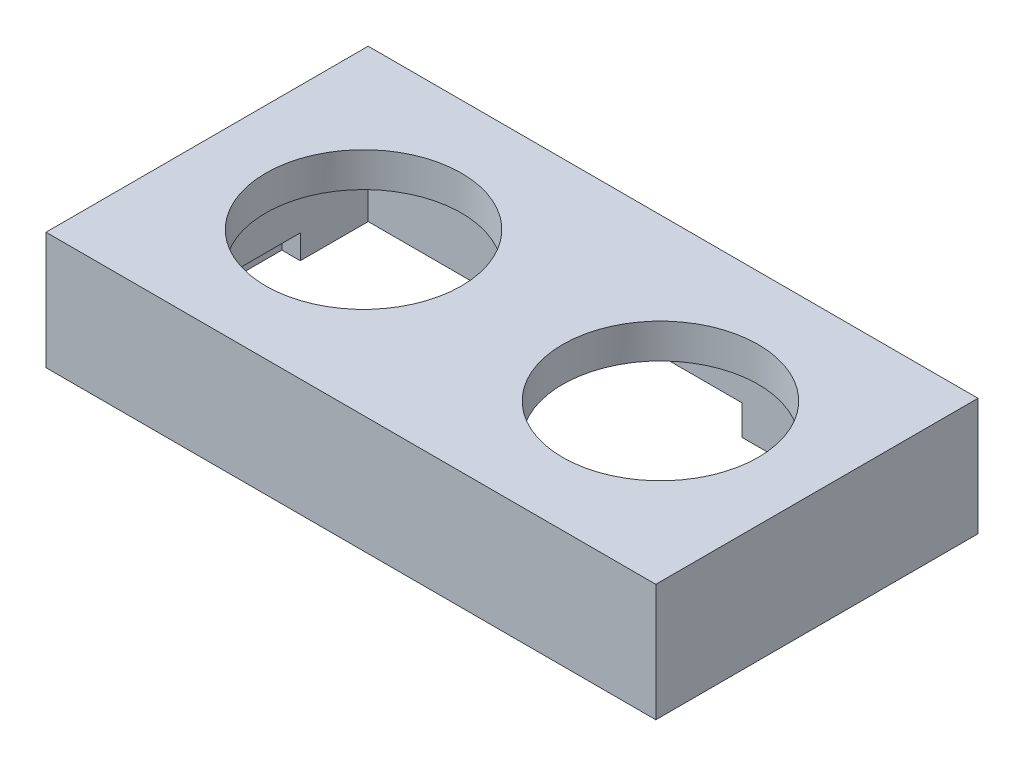
SolidWorks part; units mm, degrees
ref_plane "Front Plane" through (0, 0, 0) normal (0, 0, 1) x (1, 0, 0)
ref_plane "Top Plane" through (0, 0, 0) normal (0, 1, 0) x (1, 0, 0)
ref_plane "Right Plane" through (0, 0, 0) normal (1, 0, 0) x (0, 0, -1)
sketch "Sketch1" plane through (0, 0, 0) normal (0, 0, 1) x (1, 0, 0)
  line L0 (-44.704, 0) -> (44.704, 0) construction
  line L1 (-44.704, -25.8099) -> (44.704, -25.8099)
  line L2 (-44.704, -25.8099) -> (-44.704, 25.8099)
  line L3 (-44.704, 25.8099) -> (44.704, 25.8099)
  line L4 (44.704, -25.8099) -> (44.704, 25.8099)
  line L5 (-44.704, -25.8099) -> (44.704, 25.8099) construction
  line L6 (-44.704, 25.8099) -> (44.704, -25.8099) construction
  line L7 (-44.704, 7.8099) -> (44.704, 7.8099)
  line L8 (0, 0) -> (0, 25.8099) construction
  line L9 (-14.9309, 1.288) -> (-51.3431, 22.3106)
  line L10 (-23.5, 0.6099) -> (23.5, 0.6099)
  line L11 (-23.5, 0.6099) -> (-23.5, 15.0099)
  line L12 (-23.5, 15.0099) -> (23.5, 15.0099)
  line L13 (23.5, 0.6099) -> (23.5, 15.0099)
  line L14 (-23.5, 0.6099) -> (23.5, 15.0099) construction
  line L15 (-23.5, 15.0099) -> (23.5, 0.6099) construction
  line L16 (-23.5, 15.0099) -> (23.5, 15.0099)
  line L17 (-23.5, 15.0099) -> (-23.5, 18.0099)
  line L18 (-23.5, 18.0099) -> (23.5, 18.0099)
  line L19 (23.5, 15.0099) -> (23.5, 18.0099)
  line L20 (-14.9309, 1.288) -> (-8.5809, 12.2866)
  line L21 (-51.3431, 22.3106) -> (-44.9931, 33.3091)
  line L22 (-8.5809, 12.2866) -> (-44.9931, 33.3091)
  line L23 (-14.9309, 1.288) -> (-44.9931, 33.3091) construction
  line L24 (-51.3431, 22.3106) -> (-8.5809, 12.2866) construction
  line L25 (14.9309, 1.288) -> (51.3431, 22.3106)
  line L26 (-26.5, -2.3901) -> (26.5, -2.3901)
  line L27 (-26.5, -2.3901) -> (-26.5, 18.0099)
  line L28 (-26.5, 18.0099) -> (26.5, 18.0099)
  line L29 (26.5, -2.3901) -> (26.5, 18.0099)
  line L30 (-26.5, -2.3901) -> (26.5, 18.0099) construction
  line L31 (-26.5, 18.0099) -> (26.5, -2.3901) construction
  line L32 (8.5809, 12.2866) -> (44.9931, 33.3091)
  circle A0 centre (-44.704, 25.8099) radius 3.175
  circle A1 centre (44.704, 25.8099) radius 3.175
  circle A2 centre (-44.704, 25.8099) radius 6.35
  circle A3 centre (44.704, 25.8099) radius 6.35
  point P0 (0, 0)
  point P16 (0, 7.8099)
  point P24 (-29.962, 17.2986)
  point P25 (0, 7.8099)
  dimension "D3" = 6.35
  dimension "D4" = 6.35
  dimension "D5" = 12.7
  dimension "D6" = 12.7
  dimension "D1" = 89.408
  dimension "D2" = 30
  dimension "D7" = 18
  dimension "D8" = 47
  dimension "D9" = 7.2
  dimension "D10" = 3
  dimension "D11" = 30
  dimension "D12" = 12.7
  dimension "D13" = 53
sketch "Sketch2" plane through (0, 0, 0) normal (0, 0, 1) x (1, 0, 0)
  line L0 (-44.704, 7.8099) -> (44.704, 7.8099) construction
  line L1 (14.9309, 1.288) -> (51.3431, 22.3106) construction
  line L2 (-23.5, 15.0099) -> (23.5, 15.0099) construction
  line L3 (23.5, 0.6099) -> (23.5, 15.0099) construction
  line L5 (23.5, 7.8099) -> (26.5, 7.8099)
  line L6 (-23.5, 7.8099) -> (23.5, 7.8099)
  line L12 (-51.3431, 22.3106) -> (-14.9309, 1.288)
  line L13 (-44.9931, 33.3091) -> (-51.3431, 22.3106)
  line L14 (-8.5809, 12.2866) -> (-44.9931, 33.3091)
  line L15 (-14.9309, 1.288) -> (-8.5809, 12.2866)
  line L16 (-51.3431, 22.3106) -> (-26.5, 7.9674)
  line L18 (-18.494, 18.0099) -> (-44.9931, 33.3091)
  line L20 (-26.5, -2.3901) -> (26.5, -2.3901)
  line L21 (-26.5, 18.0099) -> (-26.5, -2.3901)
  line L22 (26.5, 18.0099) -> (-26.5, 18.0099)
  line L23 (26.5, -2.3901) -> (26.5, 18.0099)
  line L25 (-26.5, 7.9674) -> (-26.5, 7.8099)
  line L26 (18.494, 18.0099) -> (-18.494, 18.0099)
  line L27 (26.5, 7.8099) -> (26.5, 7.9674)
  line L29 (-23.5, 0.6099) -> (-23.5, 15.0099) construction
  line L30 (-23.5, 15.0099) -> (23.5, 15.0099) construction
  line L32 (-23.5, 18.0099) -> (23.5, 18.0099) construction
  line L34 (8.5809, 12.2866) -> (44.9931, 33.3091) construction
  line L35 (-26.5, 7.8099) -> (-23.5, 7.8099)
  line L36 (26.5, 7.9674) -> (51.3431, 22.3106)
  line L37 (-23.5, 15.0099) -> (23.5, 15.0099)
  line L38 (23.5, 7.8099) -> (23.5, 15.0099)
  line L40 (-23.5, 7.8099) -> (-23.5, 15.0099)
  line L41 (-23.5, 15.0099) -> (23.5, 15.0099)
  line L43 (-18.494, 18.0099) -> (18.494, 18.0099)
  line L45 (18.494, 18.0099) -> (44.9931, 33.3091)
  circle A1 centre (44.704, 25.8099) radius 7.5048
  circle A3 centre (-44.704, 25.8099) radius 7.5048
  circle A5 centre (44.704, 25.8099) radius 3.175
  circle A6 centre (44.704, 25.8099) radius 3.175
  circle A7 centre (-44.704, 25.8099) radius 3.175
  circle A8 centre (-44.704, 25.8099) radius 3.175
  dimension "D3" = 0
  dimension "D4" = 0
  dimension "D6" = 0
  dimension "D7" = 0
extrude "Boss-Extrude1" add sketch "Sketch2" along normal blind 3 contours L18 A3 L16 A8 | A3 L16 L25 L35 L40 L37 L38 L5 L27 L36 A1 L45 L26 L18 | L45 A1 L36 A6 | L40 L6 L38 L37
sketch "Sketch3" plane through (0, 18.0099, 0) normal (0, 1, 0) x (1, 0, 0)
  line L0 (0, 0) -> (0, -28) construction
  line L1 (-26.5, -3) -> (26.5, -3)
  line L2 (-26.5, -3) -> (-26.5, -28)
  line L3 (-26.5, -28) -> (26.5, -28)
  line L4 (26.5, -3) -> (26.5, -28)
  line L5 (-23.5, -14) -> (23.5, -14) construction
  line L6 (-23.5, -3) -> (23.5, -3)
  line L7 (-23.5, -3) -> (-23.5, -25)
  line L8 (-23.5, -25) -> (23.5, -25)
  line L9 (23.5, -3) -> (23.5, -25)
  line L10 (-23.5, -3) -> (23.5, -25) construction
  line L11 (-23.5, -25) -> (23.5, -3) construction
  circle A0 centre (-12.9, -14) radius 8.5
  circle A1 centre (12.9, -14) radius 8.5
  point P8 (0, -14)
  dimension "D6" = 17
  dimension "D1" = 25
  dimension "D2" = 47
  dimension "D3" = 22
  dimension "D4" = 0
  dimension "D5" = 12.9
sketch "Sketch4" plane through (0, 18.0099, 0) normal (0, 1, 0) x (1, 0, 0)
  line L4 (23.5, -3) -> (-23.5, -3)
  line L5 (23.5, -25) -> (23.5, -3)
  line L6 (-23.5, -25) -> (23.5, -25)
  line L7 (-23.5, -3) -> (-23.5, -25)
  line L8 (23.5, -3) -> (-23.5, -3)
  line L9 (23.5, -25) -> (23.5, -3)
  line L10 (-23.5, -25) -> (23.5, -25)
  line L11 (-23.5, -3) -> (-23.5, -25)
  line L12 (26.5, -3) -> (-26.5, -3)
  line L13 (26.5, -28) -> (26.5, -3)
  line L14 (-26.5, -28) -> (26.5, -28)
  line L15 (-26.5, -3) -> (-26.5, -28)
  line L16 (26.5, -3) -> (-26.5, -3)
  line L17 (26.5, -28) -> (26.5, -3)
  line L18 (-26.5, -28) -> (26.5, -28)
  line L19 (-26.5, -3) -> (-26.5, -28)
  circle A1 centre (12.9, -14) radius 8.5
  circle A2 centre (12.9, -14) radius 8.5
  circle A3 centre (-12.9, -14) radius 8.5
  circle A4 centre (-12.9, -14) radius 8.5
  dimension "D1" = 0
  dimension "D2" = 0
  dimension "D3" = 0
  dimension "D4" = 0
extrude "Boss-Extrude3" add sketch "Sketch4" against normal blind 3 contours L19 L18 L17 L16
sketch "Sketch5" plane through (0, 15.0099, 0) normal (0, -1, 0) x (1, 0, 0)
  line L4 (-23.5, 3) -> (23.5, 3)
  line L5 (23.5, 3) -> (23.5, 25)
  line L6 (23.5, 25) -> (-23.5, 25)
  line L7 (-23.5, 25) -> (-23.5, 3)
  line L8 (-23.5, 3) -> (23.5, 3)
  line L9 (23.5, 3) -> (23.5, 25)
  line L10 (23.5, 25) -> (-23.5, 25)
  line L11 (-23.5, 25) -> (-23.5, 3)
  line L12 (-26.5, 3) -> (26.5, 3)
  line L13 (26.5, 3) -> (26.5, 28)
  line L14 (26.5, 28) -> (-26.5, 28)
  line L15 (-26.5, 28) -> (-26.5, 3)
  line L16 (-26.5, 3) -> (26.5, 3)
  line L17 (26.5, 3) -> (26.5, 28)
  line L18 (26.5, 28) -> (-26.5, 28)
  line L19 (-26.5, 28) -> (-26.5, 3)
  circle A1 centre (12.9, 14) radius 8.5
  circle A2 centre (12.9, 14) radius 8.5
  circle A3 centre (-12.9, 14) radius 8.5
  circle A4 centre (-12.9, 14) radius 8.5
  line M11 (-26.5, 3) -> (26.5, 3)
  line M12 (26.5, 3) -> (26.5, 28)
  line M13 (26.5, 28) -> (-26.5, 28)
  line M14 (-26.5, 28) -> (-26.5, 3)
  dimension "D1" = 0
  dimension "D2" = 0
  dimension "D3" = 0
  dimension "D4" = 0
extrude "Boss-Extrude4" add sketch "Sketch5" along normal blind 7.2 contours L11 L10 L9 M11 M12 M13 M14
sketch "Sketch6" plane through (0, 15.0099, 0) normal (0, -1, 0) x (1, 0, 0)
  line L4 (-23.5, 3) -> (23.5, 3)
  line L5 (23.5, 3) -> (23.5, 25)
  line L6 (23.5, 25) -> (-23.5, 25)
  line L7 (-23.5, 25) -> (-23.5, 3)
  line L8 (-23.5, 3) -> (23.5, 3)
  line L9 (23.5, 3) -> (23.5, 25)
  line L10 (23.5, 25) -> (-23.5, 25)
  line L11 (-23.5, 25) -> (-23.5, 3)
  line L12 (-26.5, 3) -> (26.5, 3)
  line L13 (26.5, 3) -> (26.5, 28)
  line L14 (26.5, 28) -> (-26.5, 28)
  line L15 (-26.5, 28) -> (-26.5, 3)
  line L16 (-26.5, 3) -> (26.5, 3)
  line L17 (26.5, 3) -> (26.5, 28)
  line L18 (26.5, 28) -> (-26.5, 28)
  line L19 (-26.5, 28) -> (-26.5, 3)
  circle A1 centre (12.9, 14) radius 8.5
  circle A2 centre (12.9, 14) radius 8.5
  circle A3 centre (-12.9, 14) radius 8.5
  circle A4 centre (-12.9, 14) radius 8.5
  dimension "D1" = 0
  dimension "D2" = 0
  dimension "D3" = 0
  dimension "D4" = 0
extrude "Cut-Extrude1" cut sketch "Sketch6" against normal blind 7.2 contours A4 | A2
sketch "Sketch7" plane through (0, 7.8099, 0) normal (0, -1, 0) x (1, 0, 0)
  line L0 (-26.5, 3) -> (26.5, 3) construction
  line L1 (-9, 6) -> (9, 6)
  line L2 (-9, 6) -> (-9, 0)
  line L3 (-9, 0) -> (9, 0)
  line L4 (9, 6) -> (9, 0)
  line L5 (-9, 6) -> (9, 0) construction
  line L6 (-9, 0) -> (9, 6) construction
  line L7 (-26.5, 0) -> (26.5, 0) construction
  point P0 (0, 3)
  dimension "D1" = 18
extrude "Cut-Extrude2" cut sketch "Sketch7" against normal blind 2.6
sketch "Sketch8" plane through (0, 7.8099, 0) normal (0, -1, 0) x (1, 0, 0)
  line L0 (-23.5, 3) -> (-23.5, 25) construction
  line L1 (-25.1, 8.9) -> (-21.9, 8.9)
  line L2 (-25.1, 8.9) -> (-25.1, 19.1)
  line L3 (-25.1, 19.1) -> (-21.9, 19.1)
  line L4 (-21.9, 8.9) -> (-21.9, 19.1)
  line L5 (-25.1, 8.9) -> (-21.9, 19.1) construction
  line L6 (-25.1, 19.1) -> (-21.9, 8.9) construction
  line L7 (0, 3) -> (0, 25)
  line L8 (-26.5, 3) -> (26.5, 3) construction
  line L9 (-23.5, 25) -> (23.5, 25) construction
  line L10 (25.1, 19.1) -> (21.9, 19.1)
  line L11 (21.9, 8.9) -> (21.9, 19.1)
  line L12 (25.1, 8.9) -> (21.9, 8.9)
  line L13 (25.1, 8.9) -> (25.1, 19.1)
  point P0 (-23.5, 14)
  line M15 (-23.5, 3) -> (-23.5, 25)
  line M17 (23.5, 25) -> (23.5, 3)
  dimension "D1" = 1.6
  dimension "D2" = 10.2
extrude "Cut-Extrude3" cut sketch "Sketch8" against normal blind 2.1 contours L3 L2 L1 M15 | L12 L13 L10 M17
sketch "Sketch11" plane through (0, 0, 3) normal (0, 0, 1) x (1, 0, 0)
  line L4 (-51.3431, 22.3106) -> (-26.5, 7.9674)
  line L5 (-26.5, 7.9674) -> (-26.5, 18.0099)
  line L6 (-26.5, 18.0099) -> (-18.494, 18.0099)
  line L7 (-18.494, 18.0099) -> (-44.9931, 33.3091)
  line L8 (-51.3431, 22.3106) -> (-26.5, 7.9674)
  line L9 (-26.5, 7.9674) -> (-26.5, 18.0099)
  line L10 (-26.5, 18.0099) -> (-18.494, 18.0099)
  line L11 (-18.494, 18.0099) -> (-44.9931, 33.3091)
  line L12 (26.5, 18.0099) -> (26.5, 7.9674)
  line L13 (26.5, 7.9674) -> (51.3431, 22.3106)
  line L14 (44.9931, 33.3091) -> (18.494, 18.0099)
  line L15 (18.494, 18.0099) -> (26.5, 18.0099)
  line L16 (26.5, 18.0099) -> (26.5, 7.9674)
  line L17 (26.5, 7.9674) -> (51.3431, 22.3106)
  line L18 (44.9931, 33.3091) -> (18.494, 18.0099)
  line L19 (18.494, 18.0099) -> (26.5, 18.0099)
  arc A1 (-44.9931, 33.3091) -> (-51.3431, 22.3106) centre (-44.704, 25.8099) ccw
  arc A2 (-44.9931, 33.3091) -> (-51.3431, 22.3106) centre (-44.704, 25.8099) ccw
  arc A3 (51.3431, 22.3106) -> (44.9931, 33.3091) centre (44.704, 25.8099) ccw
  arc A4 (51.3431, 22.3106) -> (44.9931, 33.3091) centre (44.704, 25.8099) ccw
  dimension "D1" = 0
  dimension "D2" = 0
extrude "Cut-Extrude4" cut sketch "Sketch11" against normal blind 3
